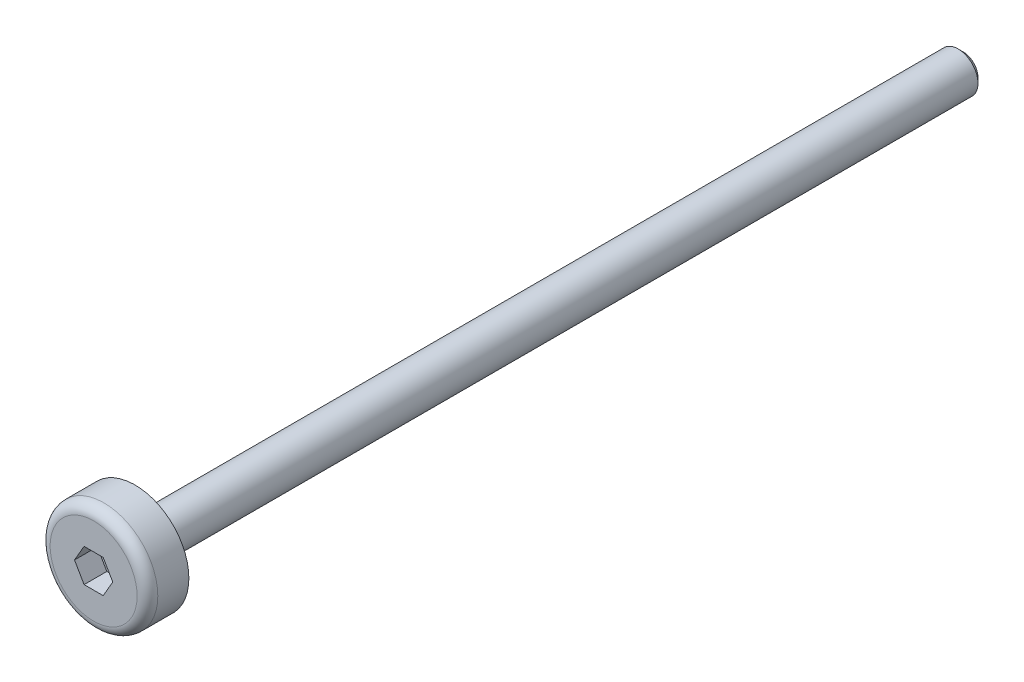
SolidWorks part; units mm, degrees
ref_plane "Front Plane" through (0, 0, 0) normal (0, 0, 1) x (1, 0, 0)
ref_plane "Top Plane" through (0, 0, 0) normal (0, 1, 0) x (1, 0, 0)
ref_plane "Right Plane" through (0, 0, 0) normal (1, 0, 0) x (0, 0, -1)
sketch "Screw Section" plane through (0, 0, 0) normal (0, 1, 0) x (1, 0, 0)
  line L0 (0, 50) -> (1.2, 50)
  line L1 (1.2, 50) -> (1.2, 0)
  line L2 (1.2, 0) -> (3.25, 0)
  line L3 (3.25, 0) -> (3.25, -2.5)
  line L4 (3.25, -2.5) -> (0, -2.5)
  line L5 (0, -2.5) -> (0, 50)
  line L6 (0, -10.123) -> (0, 10.123) construction
  dimension "D1" = 1.2
  dimension "D2" = 3.25
  dimension "D3" = 50
  dimension "D4" = 2.5
  dimension "D5" = 10.123
  dimension "D6" = 10.123
revolve "Screw Blank Revolve" add sketch "Screw Section" angle 360 about L6
chamfer "Shank Tip Chamfer" distance 0.3 1 edges at (1.2, 0, -50)
fillet "Pan Head Round" radius 0.625 1 edges at (3.25, 0, 2.5)
ref_plane "Head Crown Plane" through (0, 0, 2.5) normal (0, 0, 1) x (1, 0, 0)
sketch "Hex Drive Sketch" plane through (0, 0, 2.5) normal (0, 0, 1) x (1, 0, 0)
  line L1 (1.1547, 0) -> (0.5774, 1)
  line L2 (0.5774, 1) -> (-0.5774, 1)
  line L3 (-0.5774, 1) -> (-1.1547, 0)
  line L4 (-1.1547, 0) -> (-0.5774, -1)
  line L5 (-0.5774, -1) -> (0.5774, -1)
  line L6 (0.5774, -1) -> (1.1547, 0)
  circle A0 centre (0, 0) radius 1 construction
  dimension "D1" = 2
extrude "Hex Drive Cut" cut sketch "Hex Drive Sketch" against normal blind 1.375
equation "\"nominal_length\"= 50.0mm 'Screw length: under pan head or including flat head"
equation "\"model_shank_radius\"= 1.2mm 'Clearance envelope minor shank radius; thread is not modeled"
equation "\"head_diameter\"= 6.5mm 'Head outside diameter"
equation "\"head_height\"= 2.5mm 'Head axial height"
equation "\"drive_across_flats\"= 2mm 'Hex drive across flats"
equation "\"tip_chamfer\"= 0.3mm 'Shank tip chamfer"
equation "\"head_round\"= 0.625mm 'Pan head crown edge radius"
equation "\"drive_depth\"= 1.375mm 'Hex socket depth"
equation "\"axis_reference_halfspan\"= 10.123mm 'Half display length of the construction axis; avoids sharing a profile endpoint"
equation "\"D1@Screw Section\"= \"model_shank_radius\""
equation "\"D2@Screw Section\"= \"head_diameter\" / 2"
equation "\"D3@Screw Section\"= \"nominal_length\""
equation "\"D4@Screw Section\"= \"head_height\""
equation "\"D5@Screw Section\"= \"axis_reference_halfspan\""
equation "\"D6@Screw Section\"= \"axis_reference_halfspan\""
equation "\"full_turn\"= 360deg 'Full circular extent for revolves and patterns"
equation "\"D1@Screw Blank Revolve\"= \"full_turn\""
equation "\"D1@Shank Tip Chamfer\"= \"tip_chamfer\""
equation "\"D1@Pan Head Round\"= \"head_round\""
equation "\"D1@Head Crown Plane\"= \"head_height\""
equation "\"D1@Hex Drive Sketch\"= \"drive_across_flats\""
equation "\"D1@Hex Drive Cut\"= \"drive_depth\""
